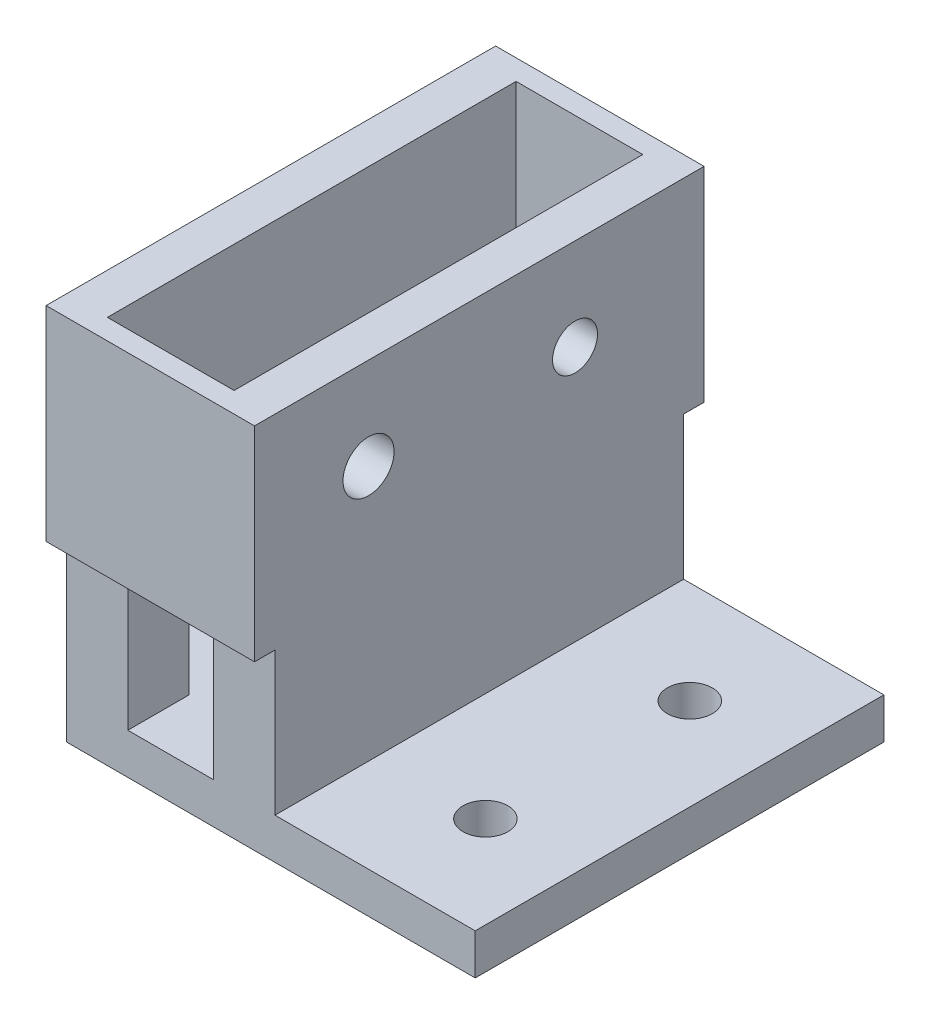
SolidWorks part; units mm, degrees
material "ABS"
ref_plane "Front Plane" through (0, 0, 0) normal (0, 0, 1) x (1, 0, 0)
ref_plane "Top Plane" through (0, 0, 0) normal (0, 1, 0) x (1, 0, 0)
ref_plane "Right Plane" through (0, 0, 0) normal (1, 0, 0) x (0, 0, -1)
sketch "Sketch1" plane through (0, 0, 0) normal (0, 0, 1) x (1, 0, 0)
  line L0 (0, 11) -> (0, -8)
  line L1 (0, 11) -> (2, 11)
  line L2 (2, 11) -> (2, 2)
  line L3 (2, 2) -> (3, 2)
  line L4 (8.2, 2) -> (8.2, 11)
  line L5 (8.2, 11) -> (10.2, 11)
  line L6 (10.2, 11) -> (10.2, -6)
  line L8 (3, 2) -> (3, -6)
  line L9 (3, -6) -> (7.2, -6)
  line L10 (7.2, -6) -> (7.2, 2)
  line L11 (7.2, 2) -> (8.2, 2)
  line L13 (10.2, -6) -> (20, -6)
  line L16 (0, -8) -> (20, -8)
  line L17 (20, -8) -> (20, -6)
  dimension "D1" = 2
  dimension "D2" = 9
  dimension "D3" = 8
  dimension "D4" = 2
  dimension "D5" = 2
  dimension "D7" = 6.2
extrude "Boss-Extrude1" add sketch "Sketch1" along normal blind 20
sketch "Sketch2" plane through (0, 0, 0) normal (-1, 0, 0) x (0, 0, 1)
  line L0 (20, -8) -> (0, -8) construction
  line L1 (3, -6) -> (17, -6)
  line L2 (3, -6) -> (3, -2)
  line L3 (3, -2) -> (17, -2)
  line L4 (17, -6) -> (17, -2)
  line L5 (0, 11) -> (0, -8) construction
  line L6 (20, 11) -> (20, -8) construction
  dimension "D1" = 2
  dimension "D2" = 3
  dimension "D3" = 3
  dimension "D4" = 4
extrude "Cut-Extrude1" cut sketch "Sketch2" against normal up to surface (3 mm away) up to face at (3, -2, 10)
sketch "Sketch3" plane through (10.2, 0, 0) normal (1, 0, 0) x (0, 0, -1)
  line L0 (-23.5125, 6.5) -> (4.7047, 6.5) construction
  line L1 (-20, 11) -> (0, 11) construction
  circle A0 centre (-15.4212, 6.5) radius 1.25
  circle A1 centre (-5.3158, 6.5) radius 1.1
  dimension "D2" = 2.5
  dimension "D3" = 2.2
  dimension "D1" = 4.5
sketch "Sketch4" plane through (0, -6, 0) normal (0, 1, 0) x (1, 0, 0)
  line L0 (15.5, 2.8795) -> (15.5, -25.1968) construction
  line L2 (20, -20) -> (20, 0) construction
  line L3 (20, 0) -> (10.2, 0) construction
  line L5 (20, -20) -> (10.2, -20) construction
  circle A0 centre (15.5, -5) radius 1.1
  circle A1 centre (15.5, -15) radius 1.1
  dimension "D4" = 2.2
  dimension "D5" = 2.2
  dimension "D1" = 4.5
  dimension "D2" = 5
  dimension "D3" = 5
extrude "Cut-Extrude2" cut sketch "Sketch4" against normal blind 20
extrude "Cut-Extrude3" cut sketch "Sketch3" against normal up to surface (2 mm away) up to face at (8.2, 6.5, 10)
sketch "Sketch9" plane through (0, 11, 0) normal (0, 1, 0) x (1, 0, 0)
  line L0 (0, 0) -> (10.2, 0)
  line L1 (10.2, 0) -> (10.2, 1)
  line L2 (10.2, 1) -> (0, 1)
  line L3 (0, 1) -> (0, 0)
  line L4 (10.2, -20) -> (0, -20)
  line L5 (0, -20) -> (0, -21)
  line L6 (0, -21) -> (10.2, -21)
  line L7 (10.2, -21) -> (10.2, -20)
  dimension "D1" = 1
  dimension "D2" = 1
extrude "Boss-Extrude11" add sketch "Sketch9" against normal blind 10
